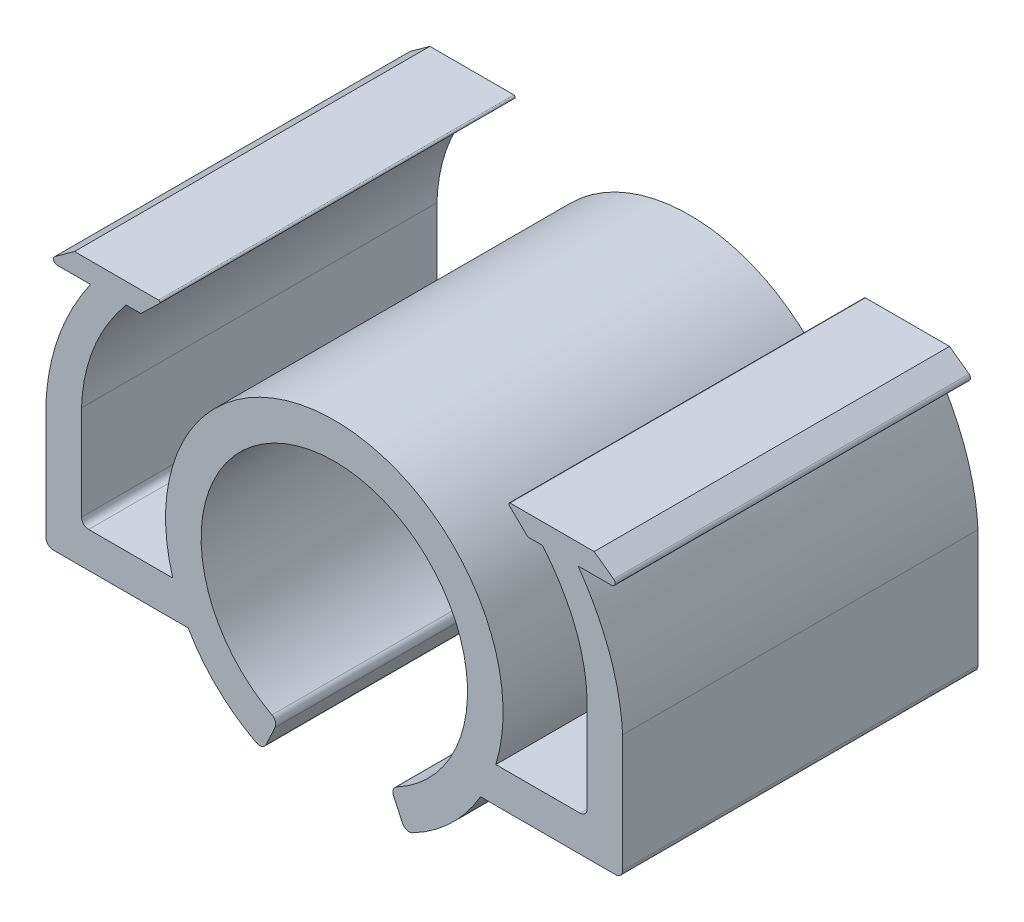
SolidWorks part; units mm, degrees
material "ABS"
ref_plane "Front Plane" through (0, 0, 0) normal (0, 0, 1) x (1, 0, 0)
ref_plane "Top Plane" through (0, 0, 0) normal (0, 1, 0) x (1, 0, 0)
ref_plane "Right Plane" through (0, 0, 0) normal (1, 0, 0) x (0, 0, -1)
sketch "Sketch2" plane through (0, 0, 0) normal (0, 0, 1) x (1, 0, 0)
  line L0 (0, 0) -> (0, 7.5722) construction
  line L1 (0, 0) -> (0, -6.0325) construction
  line L2 (0, 0) -> (-2.5487, -5.4656) construction
  line L3 (0, 6.0307) -> (0, 4.7607)
  line L4 (-2.1172, -4.5404) -> (-2.4382, -5.2288)
  line L6 (-9.2865, 6.6075) -> (-6.2847, 6.6075)
  line L7 (-6.2493, 6.5202) -> (-6.9008, 5.8886)
  line L10 (-8.7141, 5.8742) -> (-9.2865, 5.8742)
  line L17 (-6.9361, 5.8742) -> (-6.9909, 5.8742)
  line L18 (-5.2245, -3.0123) -> (-10.0505, -3.0123)
  line L20 (-5.7735, -1.7423) -> (-8.7805, -1.7423)
  line L21 (-9.9839, 6.1042) -> (-9.2865, 6.6075)
  line L35 (-10.3045, -2.7583) -> (-10.3045, 1.4438)
  line L36 (-9.0345, -1.4883) -> (-9.0345, 1.8938)
  line L49 (-9.2865, 5.8742) -> (-9.9095, 5.8742)
  line L63 (-6.9361, 5.8742) -> (-7.4441, 5.8742)
  line L64 (0, 0) -> (2.5487, -5.4656) construction
  line L65 (6.9361, 5.8742) -> (7.4441, 5.8742)
  line L66 (9.2865, 5.8742) -> (9.9095, 5.8742)
  line L67 (9.0345, -1.4883) -> (9.0345, 1.8938)
  line L68 (10.3045, -2.7583) -> (10.3045, 1.4438)
  line L69 (9.9839, 6.1042) -> (9.2865, 6.6075)
  line L70 (5.7735, -1.7423) -> (8.7805, -1.7423)
  line L71 (5.2245, -3.0123) -> (10.0505, -3.0123)
  line L72 (6.9361, 5.8742) -> (6.9909, 5.8742)
  line L73 (8.7141, 5.8742) -> (9.2865, 5.8742)
  line L74 (6.2493, 6.5202) -> (6.9008, 5.8886)
  line L75 (9.2865, 6.6075) -> (6.2847, 6.6075)
  line L76 (2.1172, -4.5404) -> (2.4382, -5.2288)
  arc A0 (2.2292, -4.2065) -> (-2.2292, -4.2065) centre (0, 0) ccw
  arc A1 (5.7735, -1.7423) -> (-5.7735, -1.7423) centre (0, 0) ccw
  arc A4 (-2.4382, -5.2288) -> (-2.7881, -5.3474) centre (-2.6699, -5.1207) cw
  arc A5 (-2.2292, -4.2065) -> (-2.1172, -4.5404) centre (-2.349, -4.4324) cw
  arc A6 (-5.2245, -3.0123) -> (-2.7881, -5.3474) centre (0, 0) ccw
  arc A8 (-10.0505, -3.0123) -> (-10.3045, -2.7583) centre (-10.0505, -2.7583) cw
  arc A12 (-6.2493, 6.5202) -> (-6.2847, 6.6075) centre (-6.2847, 6.5567) ccw
  arc A14 (-6.9008, 5.8886) -> (-6.9361, 5.8742) centre (-6.9361, 5.925) cw
  arc A26 (-9.0345, -1.4883) -> (-8.7805, -1.7423) centre (-8.7805, -1.4883) ccw
  arc A48 (-9.9839, 6.1042) -> (-9.9095, 5.8742) centre (-9.9095, 6.0012) ccw
  arc A49 (9.9839, 6.1042) -> (9.9095, 5.8742) centre (9.9095, 6.0012) cw
  arc A50 (9.0345, -1.4883) -> (8.7805, -1.7423) centre (8.7805, -1.4883) cw
  arc A51 (6.9008, 5.8886) -> (6.9361, 5.8742) centre (6.9361, 5.925) ccw
  arc A52 (6.2493, 6.5202) -> (6.2847, 6.6075) centre (6.2847, 6.5567) cw
  arc A53 (10.0505, -3.0123) -> (10.3045, -2.7583) centre (10.0505, -2.7583) ccw
  arc A54 (5.2245, -3.0123) -> (2.7881, -5.3474) centre (0, 0) cw
  arc A55 (2.2292, -4.2065) -> (2.1172, -4.5404) centre (2.349, -4.4324) ccw
  arc A56 (2.4382, -5.2288) -> (2.7881, -5.3474) centre (2.6699, -5.1207) ccw
  spline S0 degree 2 poles (-8.7141, 5.8742) (-10.1788, 3.7755) (-10.3045, 1.4438) knots 0 0 0 0.841933 0.841933 0.841933
  spline S1 degree 2 poles (7.4441, 5.8742) (8.9655, 4.0238) (9.0345, 1.8938) knots 0 0 0 0.913335 0.913335 0.913335
  spline S2 degree 2 poles (-7.4441, 5.8742) (-8.9655, 4.0238) (-9.0345, 1.8938) knots 0 0 0 0.913335 0.913335 0.913335
  spline S3 degree 2 poles (8.7141, 5.8742) (10.1788, 3.7755) (10.3045, 1.4438) knots 0 0 0 0.841933 0.841933 0.841933
  point P19 (-2.0119, -4.3146)
  point P27 (-10.3025, 5.8742)
  point P32 (-10.3025, 5.8742)
  point P33 (-9.4761, 5.8742)
  point P40 (-6.1593, 6.6075)
  point P72 (6.1593, 6.6075)
  point P73 (9.4761, 5.8742)
  point P74 (10.3025, 5.8742)
  point P75 (2.0119, -4.3146)
  dimension "D2" = 1.27
  dimension "D5" = 1.27
  dimension "D10" = 1.016
  dimension "D12" = 0.0508
  dimension "D13" = 0.254
  dimension "D6" = 0.127
  dimension "D3" = 1.016
  dimension "D4" = 4.826
  dimension "D7" = 0.762
extrude "Boss-Extrude1" add sketch "Sketch2" along normal blind 12.7
